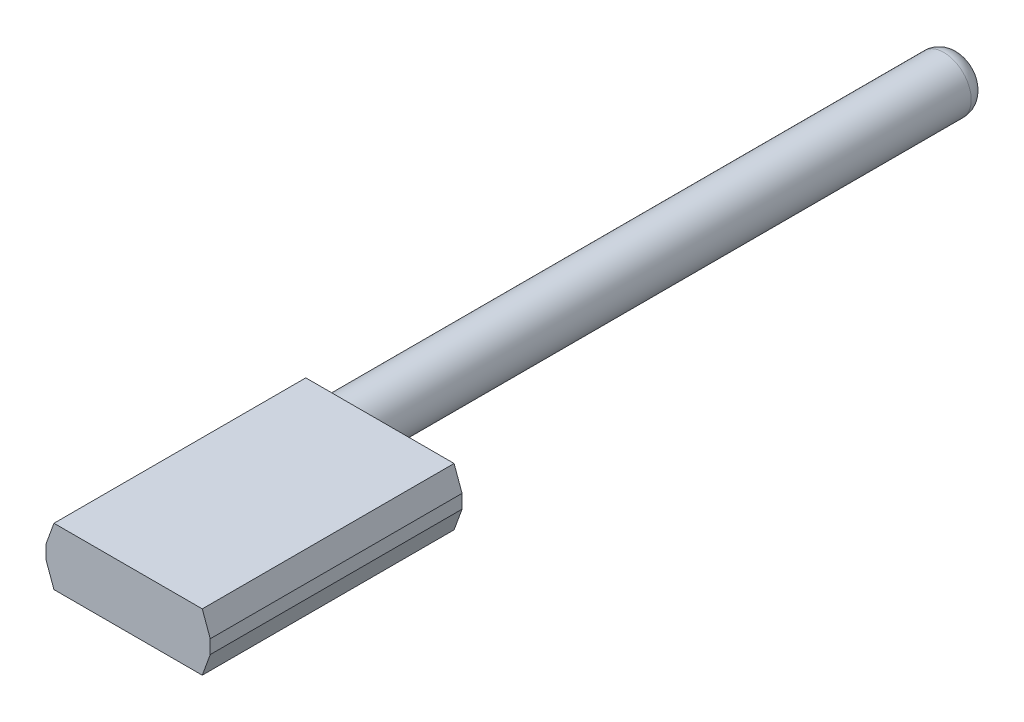
SolidWorks part; units mm, degrees
material "ABS"
ref_plane "前基準面" through (0, 0, 0) normal (0, 0, 1) x (1, 0, 0)
ref_plane "上基準面" through (0, 0, 0) normal (0, 1, 0) x (1, 0, 0)
ref_plane "右基準面" through (0, 0, 0) normal (1, 0, 0) x (0, 0, -1)
sketch "草圖1" plane through (0, 0, 0) normal (0, 0, 1) x (1, 0, 0)
  line L0 (-15, 1.25) -> (-13.5441, 5.25)
  line L1 (-13.5441, -5.25) -> (13.5441, -5.25)
  line L2 (-15, -1.25) -> (-15, 1.25)
  line L3 (-13.5441, 5.25) -> (13.5441, 5.25)
  line L4 (15, -1.25) -> (15, 1.25)
  line L5 (-15, -5.25) -> (15, 5.25) construction
  line L6 (-15, 5.25) -> (15, -5.25) construction
  line L7 (-13.5441, -5.25) -> (-15, -1.25)
  line L8 (15, 1.25) -> (13.5441, 5.25)
  line L9 (13.5441, -5.25) -> (15, -1.25)
  point P0 (0, 0)
  dimension "D1" = 30
  dimension "D2" = 10.5
  dimension "D3" = 4
  dimension "D4" = 20
  dimension "D5" = 4
  dimension "D6" = 20
  dimension "D7" = 4
  dimension "D8" = 20
  dimension "D9" = 4
  dimension "D10" = 20
extrude "填料-伸長1" add sketch "草圖1" along normal blind 46
sketch "草圖2" plane through (0, 0, 0) normal (0, 0, -1) x (-1, 0, 0)
  line L0 (-15, 0) -> (15, 0) construction
  line L1 (-15, -1.25) -> (-15, 1.25) construction
  line L2 (15, 1.25) -> (15, -1.25) construction
  circle A0 centre (7, 0) radius 5
  dimension "D2" = 10
  dimension "D1" = 8
extrude "填料-伸長2" add sketch "草圖2" along normal blind 113
fillet "圓角1" radius 3 1 edges at (-12, 0, -113)
